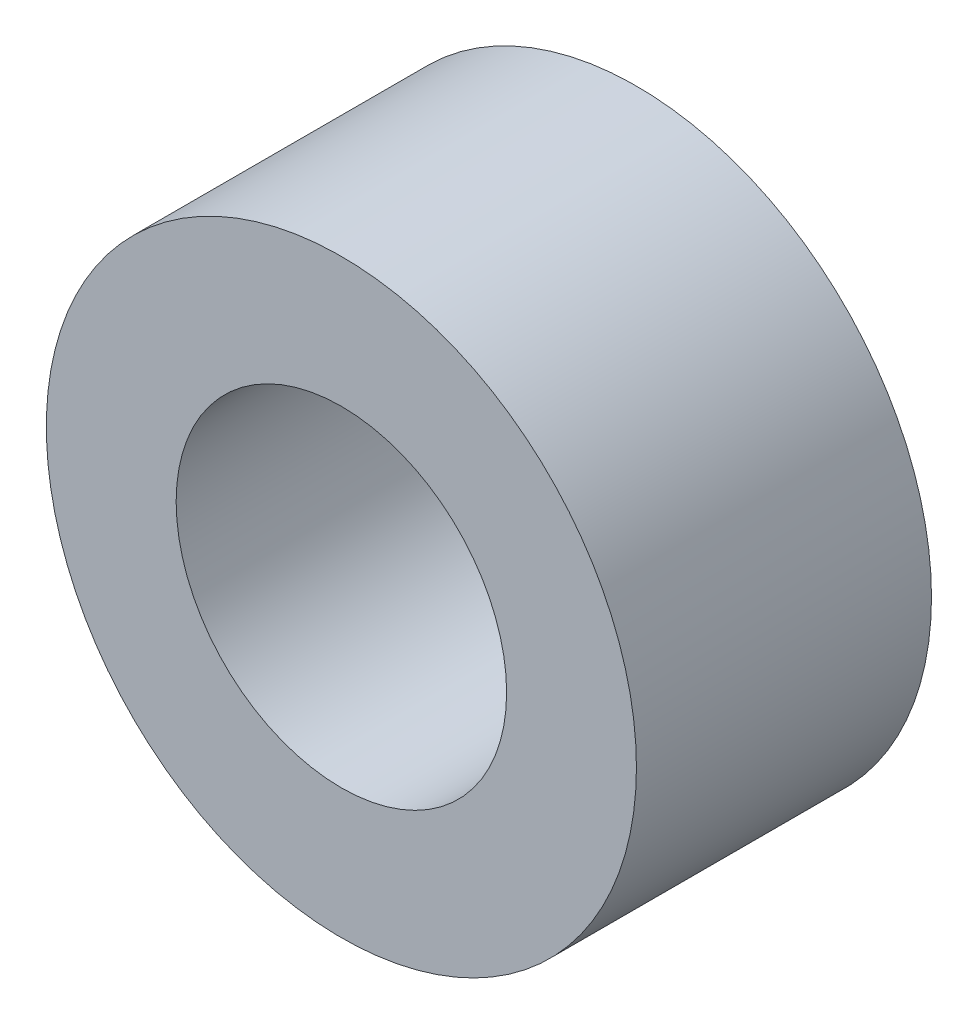
SolidWorks part; units mm, degrees
ref_plane "Front Plane" through (0, 0, 0) normal (0, 0, 1) x (1, 0, 0)
ref_plane "Top Plane" through (0, 0, 0) normal (0, 1, 0) x (1, 0, 0)
ref_plane "Right Plane" through (0, 0, 0) normal (1, 0, 0) x (0, 0, -1)
sketch "Sketch1" plane through (0, 0, 0) normal (0, 0, 1) x (1, 0, 0)
  circle A0 centre (0, 0) radius 3.175
  circle A1 centre (0, 0) radius 1.778
  dimension "OD" = 6.35
  dimension "ID" = 3.556
extrude "Extrude1" add sketch "Sketch1" along normal mid plane 3.175
sketch "Sketch2" plane through (0, 0, 0) normal (1, 0, 0) x (0, 0, -1)
  line L0 (-1.5875, -1.778) -> (1.5875, -1.778) construction
  line L3 (1.5875, 1.778) -> (-1.5875, 1.778) construction
  line L5 (-1.5875, -1.778) -> (1.5875, -1.778)
  line L6 (1.5875, 1.778) -> (-1.5875, 1.778)
sketch "Sketch4" plane through (0, 0, 1.5875) normal (0, 0, 1) x (1, 0, 0)
  line L0 (0, 0) -> (-1.2572, 1.2572)
  line L1 (0, -2.6194) -> (0, 2.6194) construction
  circle A0 centre (0, 0) radius 1.778 construction
  dimension "D1" = 45
